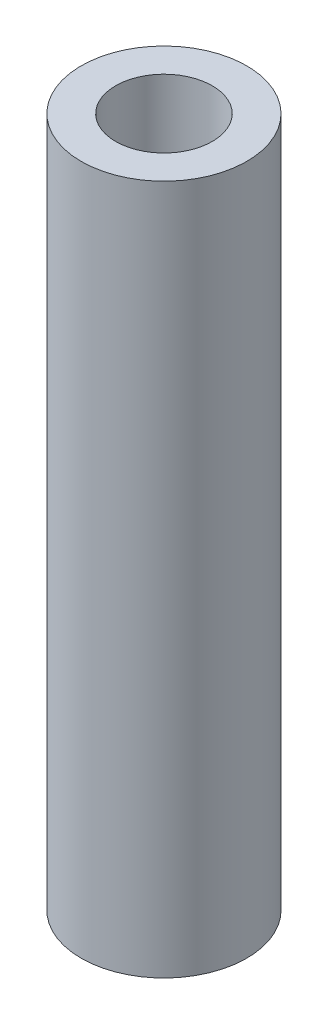
SolidWorks part; units mm, degrees
ref_plane "Спереди" through (0, 0, 0) normal (0, 0, 1) x (1, 0, 0)
ref_plane "Сверху" through (0, 0, 0) normal (0, 1, 0) x (1, 0, 0)
ref_plane "Справа" through (0, 0, 0) normal (1, 0, 0) x (0, 0, -1)
sketch "Эскиз1" plane through (0, 0, 0) normal (0, 1, 0) x (1, 0, 0)
  circle A0 centre (0, 0) radius 6
  circle A1 centre (0, 0) radius 3.5
  dimension "D1" = 7
  dimension "D2" = 12
extrude "Бобышка-Вытянуть1" add sketch "Эскиз1" along normal blind 50
